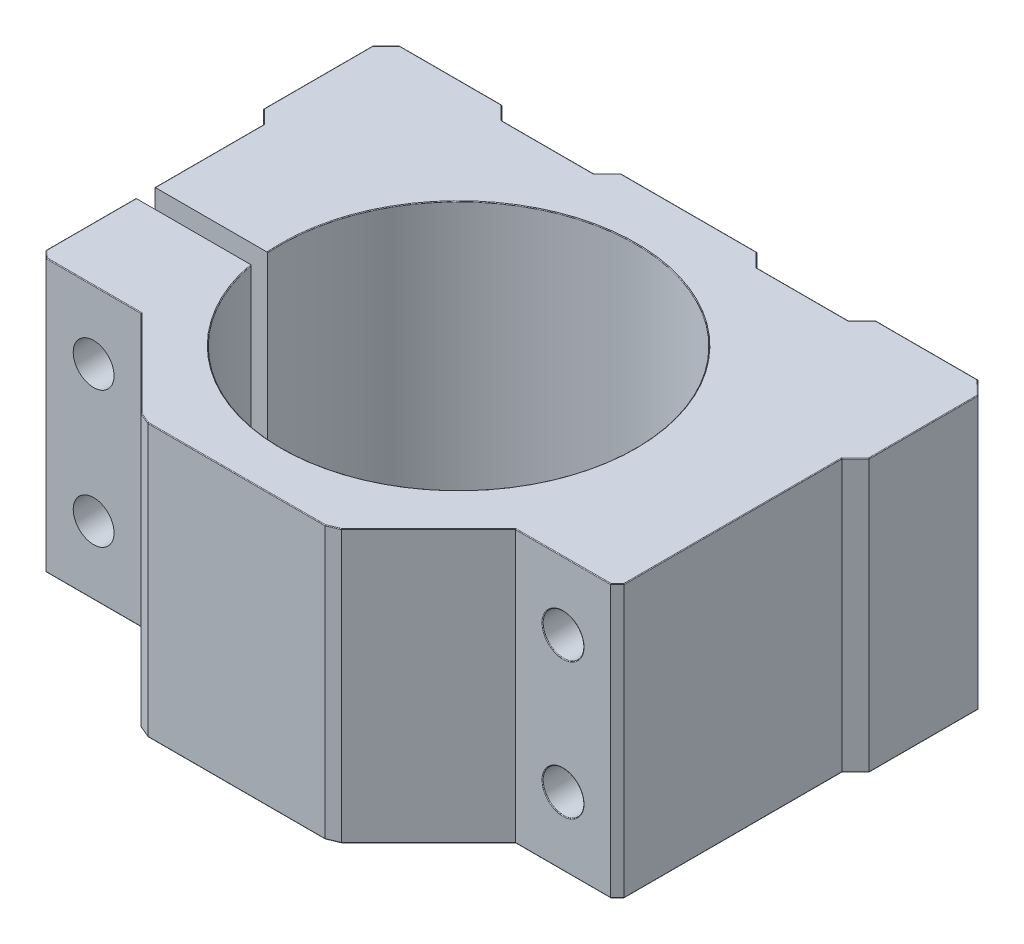
SolidWorks part; units mm, degrees
material "Liga 6061"
ref_plane "Plano frontal" through (0, 0, 0) normal (0, 0, 1) x (1, 0, 0)
ref_plane "Plano superior" through (0, 0, 0) normal (0, 1, 0) x (1, 0, 0)
ref_plane "Plano direito" through (0, 0, 0) normal (1, 0, 0) x (0, 0, -1)
sketch "Esboço1" plane through (0, 0, 0) normal (0, 1, 0) x (1, 0, 0)
  line L0 (41.5, -18) -> (42.5, -17)
  line L1 (27.5, 35) -> (25.5, 33)
  line L3 (27.5, 35) -> (42.5, 35)
  line L4 (14.7071, -30.7929) -> (13, -31.5)
  line L5 (44.5, 33) -> (44.5, 17)
  line L6 (-27.5, -18) -> (-14.7071, -30.7929)
  line L7 (-27.5, -18) -> (-41.5, -18)
  line L8 (44.5, 17) -> (42.5, 15)
  line L9 (-44.5, 17) -> (-42.5, 15)
  line L10 (-25.5, 33) -> (-12, 33)
  line L11 (27.5, -18) -> (41.5, -18)
  line L12 (-44.5, 33) -> (-44.5, 17)
  line L13 (-27.5, 35) -> (-42.5, 35)
  line L14 (-27.5, 35) -> (-25.5, 33)
  line L15 (-41.5, -18) -> (-42.5, -17)
  line L18 (27.5, -18) -> (14.7071, -30.7929)
  line L19 (13, -31.5) -> (-13, -31.5)
  line L20 (42.5, 15) -> (42.5, -17)
  line L21 (-14.7071, -30.7929) -> (-13, -31.5)
  line L22 (0, -24.87) -> (0, -31.5) construction
  line L24 (-42.5, 35) -> (-44.5, 33)
  line L25 (42.5, 35) -> (44.5, 33)
  line L26 (-10, 35) -> (-12, 33)
  line L29 (-10, 35) -> (10, 35)
  line L30 (0, 35) -> (0, 27.17) construction
  line L31 (10, 35) -> (12, 33)
  line L32 (-42.5, 15) -> (-42.5, -1)
  line L33 (12, 33) -> (25.5, 33)
  line L34 (-25.5448, -3.8) -> (-42.5, -3.8)
  line L35 (-25.931, -1) -> (-42.5, -1)
  line L36 (-42.5, -3.8) -> (-42.5, -17)
  arc A1 (-25.5448, -3.8) -> (-25.931, -1) centre (0, 1.15) ccw
  dimension "D1" = 6.63
  dimension "D2" = 7.83
extrude "Ressalto-extrusão1" add sketch "Esboço1" along normal mid plane 40
sketch "Esboço2" plane through (0, 0, 0) normal (0, 0, 1) x (1, 0, 0)
  circle A0 centre (34.5, 10) radius 3
  circle A1 centre (34.5, -10) radius 3
  circle A2 centre (-34.5, -10) radius 3
  circle A3 centre (-34.5, 10) radius 3
  point P8 (0, 0)
  dimension "D1" = 2
extrude "Corte-extrusão1" cut sketch "Esboço2" against normal through all both and the other way through all
fillet "Filete1" radius 0.1 64 edges at (34.5, -20, 18) (42, -20, 17.5) (42.5, -20, 1) (43.5, -20, -16) (44.5, -20, -25) (35, -20, -35) (26.5, -20, -34) (-18.75, -20, -33) (-26.5, -20, -34) (-35, -20, -35) (-44.5, -20, -25) (-43.5, -20, -16) (-42, -20, 17.5) (-34.5, -20, 18) (-21.1036, -20, 24.3964) (-13.8536, -20, 31.1464) (0, -20, 31.5) (13.8536, -20, 31.1464) (21.1036, -20, 24.3964) (13.8536, 20, 31.1464) (0, 20, 31.5) (-13.8536, 20, 31.1464) (-21.1036, 20, 24.3964) (-34.5, 20, 18) (-42, 20, 17.5) (-43.5, 20, -16) (-44.5, 20, -25) (-35, 20, -35) (-26.5, 20, -34) (-18.75, 20, -33) (26.5, 20, -34) (35, 20, -35) (44.5, 20, -25) (43.5, 20, -16) (42.5, 20, 1) (42, 20, 17.5) (34.5, 20, 18) (21.1036, 20, 24.3964) (-31.5, -10, -35) (-37.5, 10, -35) (31.5, -10, -35) (37.5, 10, -35) (31.5, 10, 18) (31.5, -10, 18) (43.5, -20, -34) (18.75, -20, -33) (11, -20, -34) (0, -20, -35) (-11, -20, -34) (-43.5, -20, -34) (-42.5, -20, -7) (25.776, -20, -4.7052) (-42.5, -20, 10.4) (-42.5, 20, 10.4) (25.776, 20, -4.7052) (-42.5, 20, -7) (-43.5, 20, -34) (-11, 20, -34) (0, 20, -35) (11, 20, -34) (18.75, 20, -33) (43.5, 20, -34) (-37.5, 10, 1) (-37.5, -10, 1)
